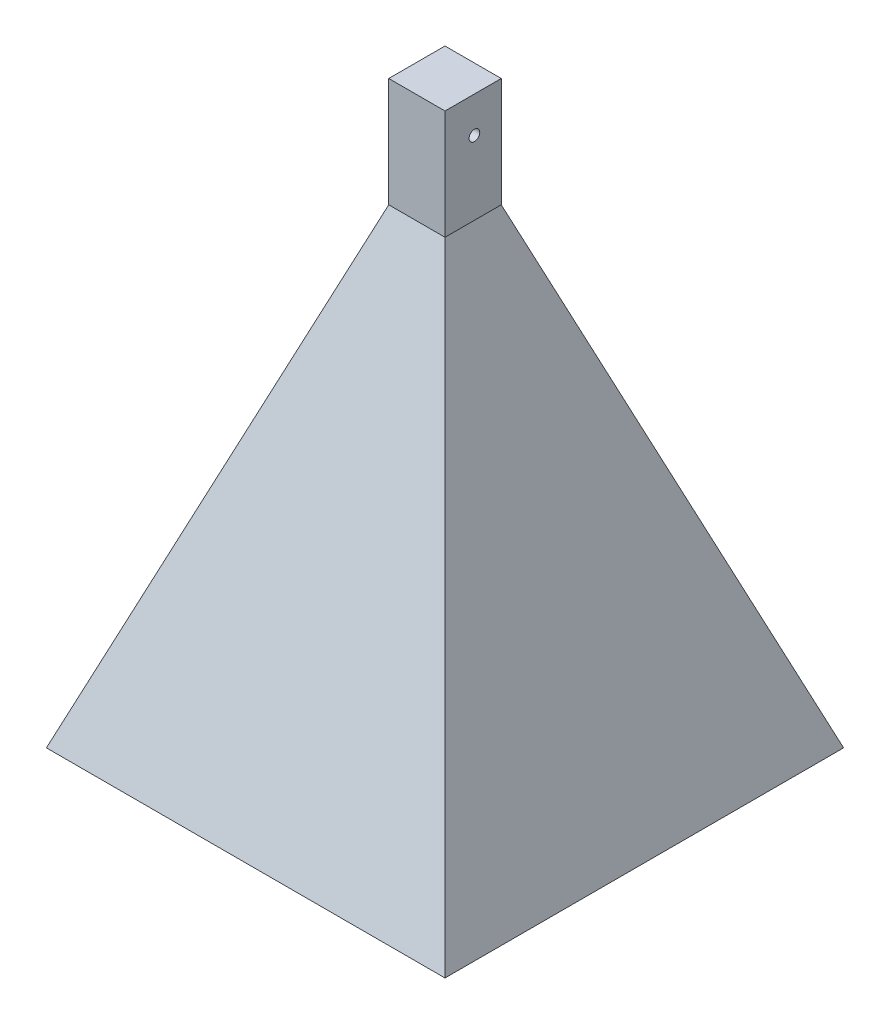
SolidWorks part; units mm, degrees
ref_plane "Front Plane" through (0, 0, 0) normal (0, 0, 1) x (1, 0, 0)
ref_plane "Top Plane" through (0, 0, 0) normal (0, 1, 0) x (1, 0, 0)
ref_plane "Right Plane" through (0, 0, 0) normal (1, 0, 0) x (0, 0, -1)
sketch "Sketch1" plane through (0, 0, 0) normal (0, 1, 0) x (1, 0, 0)
  line L1 (-372, -372) -> (372, -372)
  line L2 (-372, -372) -> (-372, 372)
  line L3 (-372, 372) -> (372, 372)
  line L4 (372, -372) -> (372, 372)
  line L5 (-372, -372) -> (372, 372) construction
  line L6 (-372, 372) -> (372, -372) construction
  point P0 (0, 0)
  dimension "D1" = 744
  dimension "D2" = 744
extrude "Boss-Extrude1" add sketch "Sketch1" along normal blind 1220 draft 20
ref_plane "Plane1" through (0, 1015, 0) normal (0, 1, 0) x (1, 0, 0)
sketch "Sketch3" plane through (0, 1015, 0) normal (0, 1, 0) x (1, 0, 0)
  line L1 (-166.4452, -112.0731) -> (166.4452, -112.0731)
  line L2 (-166.4452, -112.0731) -> (-166.4452, 112.0731)
  line L3 (-166.4452, 112.0731) -> (166.4452, 112.0731)
  line L4 (166.4452, -112.0731) -> (166.4452, 112.0731)
  line L5 (-166.4452, -112.0731) -> (166.4452, 112.0731) construction
  line L6 (-166.4452, 112.0731) -> (166.4452, -112.0731) construction
  point P0 (0, 0)
extrude "Cut-Extrude1" cut sketch "Sketch3" along normal blind 251
sketch "Sketch2" plane through (0, 1015, 0) normal (0, 1, 0) x (1, 0, 0)
  line L10 (-52.5, -52.5) -> (52.5, -52.5)
  line L11 (-52.5, -52.5) -> (-52.5, 52.5)
  line L12 (-52.5, 52.5) -> (52.5, 52.5)
  line L13 (52.5, -52.5) -> (52.5, 52.5)
  line L14 (-52.5, -52.5) -> (52.5, 52.5) construction
  line L16 (-52.5, 52.5) -> (52.5, -52.5) construction
  point P0 (0, 0)
  dimension "D1" = 105
  dimension "D2" = 105
extrude "Boss-Extrude2" add sketch "Sketch2" along normal blind 67 and the other way up to body separate body
sketch "Sketch5" plane through (0, 0, 0) normal (0, -1, 0) x (1, 0, 0)
  line L16 (342, -342) -> (342, 342)
  line L17 (342, 342) -> (-342, 342)
  line L18 (-342, 342) -> (-342, -342)
  line L19 (-342, -342) -> (342, -342)
  line L20 (342, -342) -> (342, 342)
  line L21 (342, 342) -> (-342, 342)
  line L22 (-342, 342) -> (-342, -342)
  line L23 (-342, -342) -> (342, -342)
  dimension "D1" = 30
extrude "Cut-Extrude3" cut sketch "Sketch5" against normal blind 871 draft 20
sketch "Sketch7" plane through (0, 871, 0) normal (0, -1, 0) x (1, 0, 0)
  line L16 (-24.9819, -24.9819) -> (24.9819, -24.9819)
  line L17 (24.9819, -24.9819) -> (24.9819, 24.9819)
  line L18 (24.9819, 24.9819) -> (-24.9819, 24.9819)
  line L19 (-24.9819, 24.9819) -> (-24.9819, -24.9819)
  line L20 (-24.9819, -24.9819) -> (24.9819, -24.9819)
  line L21 (24.9819, -24.9819) -> (24.9819, 24.9819)
  line L22 (24.9819, 24.9819) -> (-24.9819, 24.9819)
  line L23 (-24.9819, 24.9819) -> (-24.9819, -24.9819)
  dimension "D1" = 0
extrude "Cut-Extrude5" cut sketch "Sketch7" against normal blind 201
sketch "Sketch8" plane through (52.5, 0, 0) normal (1, 0, 0) x (0, 0, -1)
  line L0 (409.2, 1015) -> (-409.2, 1015) construction
  line L2 (52.5, 877.819) -> (52.5, 1082) construction
  circle A0 centre (2.3906, 1015) radius 10
  dimension "D1" = 20
  dimension "D2" = 50.1094
extrude "Cut-Extrude6" cut sketch "Sketch8" against normal blind 70
